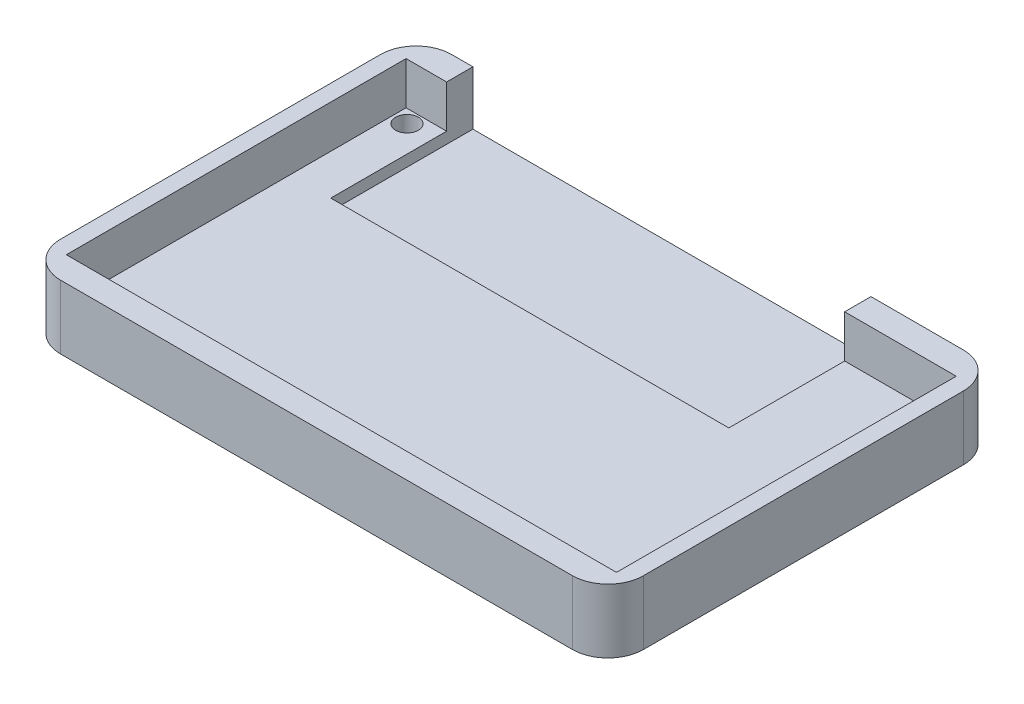
SolidWorks part; units mm, degrees
ref_plane "Front Plane" through (0, 0, 0) normal (0, 0, 1) x (1, 0, 0)
ref_plane "Top Plane" through (0, 0, 0) normal (0, 1, 0) x (1, 0, 0)
ref_plane "Right Plane" through (0, 0, 0) normal (1, 0, 0) x (0, 0, -1)
sketch "Sketch2" plane through (0, 0, 0) normal (0, 1, 0) x (1, 0, 0)
  line L13 (-52.07, 34.925) -> (52.07, 34.925)
  line L14 (-52.07, 34.925) -> (-52.07, -34.925)
  line L15 (-52.07, -34.925) -> (52.07, -34.925)
  line L16 (52.07, 34.925) -> (52.07, -34.925)
  point P4 (0, 34.925)
  point P5 (-52.07, 0)
  dimension "D1" = 104.14
  dimension "D2" = 69.85
extrude "Boss-Extrude1" add sketch "Sketch2" along normal blind 11.43
sketch "Sketch3" plane through (0, 11.43, 0) normal (0, 1, 0) x (1, 0, 0)
  line L0 (-52.07, 34.925) -> (-52.07, -34.925) construction
  line L1 (-41.91, 9.525) -> (29.21, 9.525)
  line L2 (-41.91, 9.525) -> (-41.91, 37.7046)
  line L3 (-41.91, 37.7046) -> (29.21, 37.7046)
  line L4 (29.21, 9.525) -> (29.21, 37.7046)
  line L5 (52.07, 34.925) -> (-52.07, 34.925) construction
  dimension "D1" = 10.16
  dimension "D2" = 71.12
  dimension "D3" = 25.4
extrude "Cut-Extrude1" cut sketch "Sketch3" against normal blind 9.652
sketch "Sketch4" plane through (0, 11.43, 0) normal (0, 1, 0) x (1, 0, 0)
  line L1 (-49.149, 30.226) -> (49.149, 30.226)
  line L2 (-49.149, 30.226) -> (-49.149, -30.226)
  line L4 (49.149, 30.226) -> (49.149, -30.226)
  line L5 (-49.149, 30.48) -> (49.149, 30.48)
  line L6 (-49.149, 30.48) -> (-49.149, -30.48)
  line L7 (-49.149, -30.48) -> (49.149, -30.48)
  line L8 (49.149, 30.48) -> (49.149, -30.48)
  point P6 (-49.149, 0)
  point P11 (-49.149, 0)
  point P12 (0, 30.48)
  line M6 (-41.91, 9.525) -> (-41.91, 34.925)
  line M12 (29.21, 34.925) -> (29.21, 9.525)
  line M13 (29.21, 9.525) -> (-41.91, 9.525)
  dimension "D1" = 60.452
  dimension "D2" = 98.298
  dimension "D3" = 98.298
  dimension "D4" = 60.96
extrude "Cut-Extrude2" cut sketch "Sketch4" against normal blind 7.62 contours L8 L5 L6 L7 M12 M13 M6
sketch "Sketch5" plane through (0, 11.43, 0) normal (0, 1, 0) x (1, 0, 0)
  line L0 (-6.2865, 0) -> (6.2865, 0) construction
  circle A0 centre (-46.609, 27.8447) radius 2.032
  circle A1 centre (46.609, 27.8447) radius 2.032
  circle A2 centre (46.609, -27.8447) radius 2.032
  circle A3 centre (-46.609, -27.8447) radius 2.032
  dimension "D3" = 4.064
  dimension "D1" = 93.218
  dimension "D2" = 46.609
  dimension "D4" = 27.8447
extrude "Cut-Extrude3" cut sketch "Sketch5" against normal blind 12.7
fillet "Fillet1" radius 6.35 4 edges at (-52.07, 5.715, -34.925) (-52.07, 5.715, 34.925) (52.07, 5.715, -34.925) (52.07, 5.715, 34.925)
